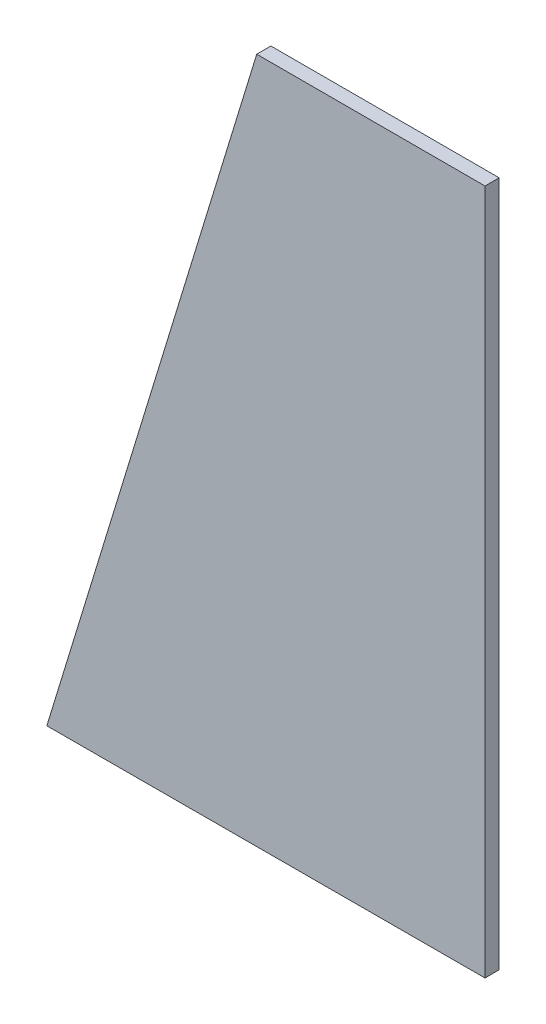
SolidWorks part; units mm, degrees
ref_plane "Front Plane" through (0, 0, 0) normal (0, 0, 1) x (1, 0, 0)
ref_plane "Top Plane" through (0, 0, 0) normal (0, 1, 0) x (1, 0, 0)
ref_plane "Right Plane" through (0, 0, 0) normal (1, 0, 0) x (0, 0, -1)
sketch "Sketch1" plane through (0, 0, 0) normal (0, 0, 1) x (1, 0, 0)
  line L0 (334.3356, 2062.48) -> (20.3086, 2061.9997)
  line L1 (20.3086, 2061.9997) -> (170.7374, 2554.0299)
  line L2 (170.7374, 2554.0299) -> (334.3356, 2554.0299)
  line L3 (334.3356, 2062.48) -> (334.3356, 2554.0299)
extrude "Boss-Extrude1" add sketch "Sketch1" along normal blind 10.16
